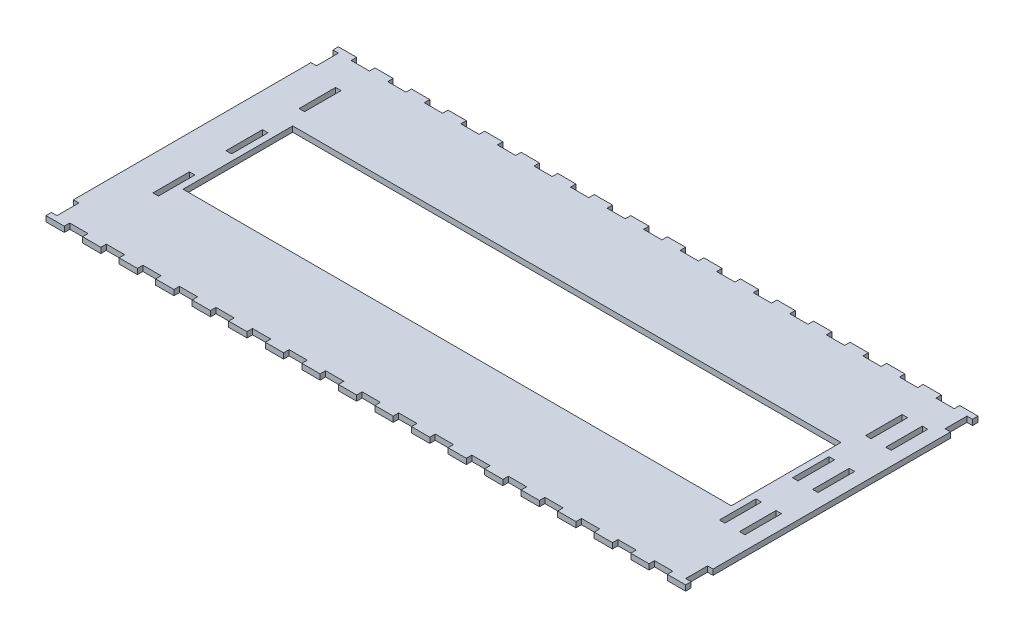
SolidWorks part; units mm, degrees
ref_plane "Alzado" through (0, 0, 0) normal (0, 0, 1) x (1, 0, 0)
ref_plane "Planta" through (0, 0, 0) normal (0, 1, 0) x (1, 0, 0)
ref_plane "Vista lateral" through (0, 0, 0) normal (1, 0, 0) x (0, 0, -1)
sketch "Croquis1" plane through (0, 0, 0) normal (0, 1, 0) x (1, 0, 0)
  line L0 (155, -80) -> (162, -80)
  line L1 (-65, 0) -> (41.2469, 0) construction
  line L2 (-10, 30) -> (-10, -35.1141) construction
  line L3 (162, -65.0029) -> (162, -77)
  line L4 (165, -80) -> (-185, 80) construction
  line L5 (165, 80) -> (-185, -80) construction
  line L6 (155, -77) -> (155, -80)
  line L7 (145, -77) -> (155, -77)
  line L8 (145, -80) -> (145, -77)
  line L9 (135, -80) -> (145, -80)
  line L10 (135, -77) -> (135, -80)
  line L11 (125, -77) -> (135, -77)
  line L12 (125, -80) -> (125, -77)
  line L13 (115, -80) -> (125, -80)
  line L14 (115, -77) -> (115, -80)
  line L15 (105, -77) -> (115, -77)
  line L16 (105, -80) -> (105, -77)
  line L17 (95, -80) -> (105, -80)
  line L18 (95, -77) -> (95, -80)
  line L19 (85, -77) -> (95, -77)
  line L20 (85, -80) -> (85, -77)
  line L21 (75, -80) -> (85, -80)
  line L22 (75, -77) -> (75, -80)
  line L23 (65, -77) -> (75, -77)
  line L24 (65, -80) -> (65, -77)
  line L25 (55, -80) -> (65, -80)
  line L26 (55, -77) -> (55, -80)
  line L27 (45, -77) -> (55, -77)
  line L28 (45, -80) -> (45, -77)
  line L29 (35, -80) -> (45, -80)
  line L30 (35, -77) -> (35, -80)
  line L31 (25, -77) -> (35, -77)
  line L32 (25, -80) -> (25, -77)
  line L33 (15, -80) -> (25, -80)
  line L34 (15, -77) -> (15, -80)
  line L35 (5, -77) -> (15, -77)
  line L36 (5, -80) -> (5, -77)
  line L37 (-5, -80) -> (5, -80)
  line L38 (-5, -77) -> (-5, -80)
  line L39 (-15, -77) -> (-5, -77)
  line L40 (-15, -80) -> (-15, -77)
  line L41 (-25, -80) -> (-15, -80)
  line L42 (-25, -77) -> (-25, -80)
  line L43 (-35, -77) -> (-25, -77)
  line L44 (-35, -80) -> (-35, -77)
  line L45 (-45, -80) -> (-35, -80)
  line L46 (-45, -77) -> (-45, -80)
  line L47 (-55, -77) -> (-45, -77)
  line L48 (-55, -80) -> (-55, -77)
  line L49 (-65, -80) -> (-55, -80)
  line L50 (-65, -77) -> (-65, -80)
  line L51 (-75, -77) -> (-65, -77)
  line L52 (-75, -80) -> (-75, -77)
  line L53 (-85, -80) -> (-75, -80)
  line L54 (-85, -77) -> (-85, -80)
  line L55 (-95, -77) -> (-85, -77)
  line L56 (-95, -80) -> (-95, -77)
  line L57 (-105, -80) -> (-95, -80)
  line L58 (-105, -77) -> (-105, -80)
  line L59 (-115, -77) -> (-105, -77)
  line L60 (-115, -80) -> (-115, -77)
  line L61 (-125, -80) -> (-115, -80)
  line L62 (-125, -77) -> (-125, -80)
  line L63 (-135, -77) -> (-125, -77)
  line L64 (-135, -80) -> (-135, -77)
  line L65 (-145, -80) -> (-135, -80)
  line L66 (-145, -77) -> (-145, -80)
  line L67 (-155, -77) -> (-145, -77)
  line L68 (-165, -77) -> (-165, -80)
  line L69 (-175, -77) -> (-165, -77)
  line L70 (-175, -80) -> (-175, -77)
  line L71 (-155, -80) -> (-155, -77)
  line L72 (-165, -80) -> (-155, -80)
  line L73 (-182, -80) -> (-175, -80)
  line L74 (-182, 80) -> (-175, 80)
  line L75 (-165, 80) -> (-155, 80)
  line L76 (-155, 80) -> (-155, 77)
  line L77 (-175, 80) -> (-175, 77)
  line L78 (-175, 77) -> (-165, 77)
  line L79 (-165, 77) -> (-165, 80)
  line L80 (-155, 77) -> (-145, 77)
  line L81 (-145, 77) -> (-145, 80)
  line L82 (-145, 80) -> (-135, 80)
  line L83 (-135, 80) -> (-135, 77)
  line L84 (-135, 77) -> (-125, 77)
  line L85 (-125, 77) -> (-125, 80)
  line L86 (-125, 80) -> (-115, 80)
  line L87 (-115, 80) -> (-115, 77)
  line L88 (-115, 77) -> (-105, 77)
  line L89 (-105, 77) -> (-105, 80)
  line L90 (-105, 80) -> (-95, 80)
  line L91 (-95, 80) -> (-95, 77)
  line L92 (-95, 77) -> (-85, 77)
  line L93 (-85, 77) -> (-85, 80)
  line L94 (-85, 80) -> (-75, 80)
  line L95 (-75, 80) -> (-75, 77)
  line L96 (-75, 77) -> (-65, 77)
  line L97 (-65, 77) -> (-65, 80)
  line L98 (-65, 80) -> (-55, 80)
  line L99 (-55, 80) -> (-55, 77)
  line L100 (-55, 77) -> (-45, 77)
  line L101 (-45, 77) -> (-45, 80)
  line L102 (-45, 80) -> (-35, 80)
  line L103 (-35, 80) -> (-35, 77)
  line L104 (-35, 77) -> (-25, 77)
  line L105 (-25, 77) -> (-25, 80)
  line L106 (-25, 80) -> (-15, 80)
  line L107 (-15, 80) -> (-15, 77)
  line L108 (-15, 77) -> (-5, 77)
  line L109 (-5, 77) -> (-5, 80)
  line L110 (-5, 80) -> (5, 80)
  line L111 (5, 80) -> (5, 77)
  line L112 (5, 77) -> (15, 77)
  line L113 (15, 77) -> (15, 80)
  line L114 (15, 80) -> (25, 80)
  line L115 (25, 80) -> (25, 77)
  line L116 (25, 77) -> (35, 77)
  line L117 (35, 77) -> (35, 80)
  line L118 (35, 80) -> (45, 80)
  line L119 (45, 80) -> (45, 77)
  line L120 (45, 77) -> (55, 77)
  line L121 (55, 77) -> (55, 80)
  line L122 (55, 80) -> (65, 80)
  line L123 (65, 80) -> (65, 77)
  line L124 (65, 77) -> (75, 77)
  line L125 (75, 77) -> (75, 80)
  line L126 (75, 80) -> (85, 80)
  line L127 (85, 80) -> (85, 77)
  line L128 (85, 77) -> (95, 77)
  line L129 (95, 77) -> (95, 80)
  line L130 (95, 80) -> (105, 80)
  line L131 (105, 80) -> (105, 77)
  line L132 (105, 77) -> (115, 77)
  line L133 (115, 77) -> (115, 80)
  line L134 (115, 80) -> (125, 80)
  line L135 (125, 80) -> (125, 77)
  line L136 (125, 77) -> (135, 77)
  line L137 (135, 77) -> (135, 80)
  line L138 (135, 80) -> (145, 80)
  line L139 (145, 80) -> (145, 77)
  line L140 (145, 77) -> (155, 77)
  line L141 (155, 77) -> (155, 80)
  line L142 (155, 80) -> (162, 80)
  line L143 (165, -65.0029) -> (162, -65.0029)
  line L144 (162, 64.9971) -> (162, 77)
  line L145 (165, 64.9971) -> (162, 64.9971)
  line L146 (165, -65.0029) -> (165, 64.9971)
  line L147 (-182, -80) -> (-185, -80)
  line L148 (-185, -80) -> (-185, -77)
  line L149 (-185, -77) -> (-182, -77)
  line L150 (-182, 80) -> (-185, 80)
  line L151 (-185, 80) -> (-185, 77)
  line L152 (-185, 77) -> (-182, 77)
  line L153 (162, -80) -> (165, -80)
  line L154 (165, -80) -> (165, -77)
  line L155 (165, -77) -> (162, -77)
  line L156 (165, 77) -> (162, 77)
  line L157 (165, 80) -> (165, 77)
  line L158 (162, 80) -> (165, 80)
  line L159 (-166.5, -40.0029) -> (-163.5, -40.0029)
  line L160 (150.5, 59.9971) -> (150.5, -44.051) construction
  line L161 (140, -30) -> (140, 30)
  line L162 (154.5, -40.0029) -> (157.5, -40.0029)
  line L163 (-160, -30) -> (-160, 30)
  line L164 (140, -37.5) -> (-160, 37.5) construction
  line L165 (140, 37.5) -> (-160, -37.5) construction
  line L166 (-166.5, 59.9971) -> (-163.5, 59.9971)
  line L167 (-166.5, 59.9971) -> (-166.5, 39.9971)
  line L168 (-166.5, -20.0029) -> (-166.5, -40.0029)
  line L169 (-163.5, 59.9971) -> (-163.5, 39.9971)
  line L170 (-166.5, 59.9971) -> (-163.5, -60.0029) construction
  line L171 (-166.5, -60.0029) -> (-163.5, 59.9971) construction
  line L172 (-166.5, -20.0029) -> (-163.5, -20.0029)
  line L173 (-185, -65.0029) -> (-185, 64.9971)
  line L174 (-166.5, -0.0029) -> (-163.5, -0.0029)
  line L175 (-185, 64.9971) -> (-182, 64.9971)
  line L176 (-182, 64.9971) -> (-182, 77)
  line L177 (-185, -65.0029) -> (-182, -65.0029)
  line L178 (-182, -65.0029) -> (-182, -77)
  line L179 (-166.5, 19.9971) -> (-163.5, 19.9971)
  line L180 (-166.5, 39.9971) -> (-163.5, 39.9971)
  line L181 (-163.5, -20.0029) -> (-163.5, -40.0029)
  line L182 (-166.5, 19.9971) -> (-166.5, -0.0029)
  line L183 (-163.5, 19.9971) -> (-163.5, -0.0029)
  line L184 (143.5, 19.9971) -> (143.5, -0.0029)
  line L185 (146.5, 19.9971) -> (146.5, -0.0029)
  line L186 (143.5, -20.0029) -> (143.5, -40.0029)
  line L187 (146.5, 39.9971) -> (143.5, 39.9971)
  line L188 (146.5, 19.9971) -> (143.5, 19.9971)
  line L189 (146.5, -0.0029) -> (143.5, -0.0029)
  line L190 (146.5, -20.0029) -> (143.5, -20.0029)
  line L191 (143.5, 59.9971) -> (143.5, 39.9971)
  line L192 (146.5, -20.0029) -> (146.5, -40.0029)
  line L193 (146.5, 59.9971) -> (146.5, 39.9971)
  line L194 (146.5, 59.9971) -> (143.5, 59.9971)
  line L195 (146.5, -40.0029) -> (143.5, -40.0029)
  line L196 (-160, -30) -> (140, -30)
  line L197 (-160, 30) -> (140, 30)
  line L198 (154.5, 59.9971) -> (157.5, 59.9971)
  line L199 (154.5, 59.9971) -> (154.5, 39.9971)
  line L200 (154.5, -20.0029) -> (154.5, -40.0029)
  line L201 (157.5, 59.9971) -> (157.5, 39.9971)
  line L202 (154.5, -20.0029) -> (157.5, -20.0029)
  line L203 (154.5, -0.0029) -> (157.5, -0.0029)
  line L204 (154.5, 19.9971) -> (157.5, 19.9971)
  line L205 (154.5, 39.9971) -> (157.5, 39.9971)
  line L206 (157.5, -20.0029) -> (157.5, -40.0029)
  line L207 (154.5, 19.9971) -> (154.5, -0.0029)
  line L208 (157.5, 19.9971) -> (157.5, -0.0029)
  point P0 (-10, 0)
  point P149 (165, -0.0029)
  point P158 (-10, 0)
  point P163 (-165, -0.0029)
  point P180 (-185, -0.0029)
  point P199 (145, -0.0029)
  point P218 (156, -0.0029)
  dimension "D1" = 160
  dimension "D2" = 350
  dimension "D3" = 75
  dimension "D4" = 300
  dimension "D5" = 3.5
  dimension "D6" = 20
  dimension "D7" = 20
  dimension "D8" = 20
  dimension "D9" = 20
  dimension "D10" = 20
  dimension "D11" = 17.0029
  dimension "D12" = 30
  dimension "D13" = 30
  dimension "D14" = 25
  dimension "D15" = 25
  dimension "D16" = 8
extrude "Saliente-Extruir1" add sketch "Croquis1" along normal blind 3
